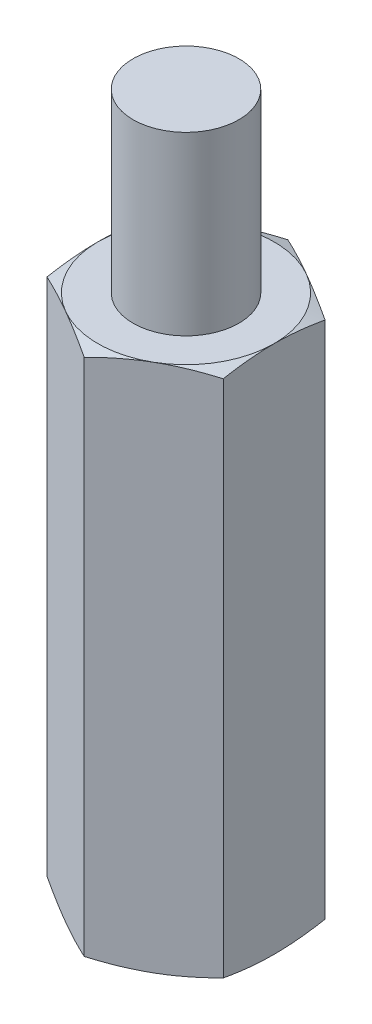
SolidWorks part; units mm, degrees
ref_plane "Front Plane" through (0, 0, 0) normal (0, 0, 1) x (1, 0, 0)
ref_plane "Top Plane" through (0, 0, 0) normal (0, 1, 0) x (1, 0, 0)
ref_plane "Right Plane" through (0, 0, 0) normal (1, 0, 0) x (0, 0, -1)
sketch "Sketch1" plane through (0, 0, 0) normal (0, 1, 0) x (1, 0, 0)
  line L1 (0, 2.8868) -> (-2.5, 1.4434)
  line L2 (-2.5, 1.4434) -> (-2.5, -1.4434)
  line L3 (-2.5, -1.4434) -> (0, -2.8868)
  line L4 (0, -2.8868) -> (2.5, -1.4434)
  line L5 (2.5, -1.4434) -> (2.5, 1.4434)
  line L6 (2.5, 1.4434) -> (0, 2.8868)
  circle A0 centre (0, 0) radius 2.5 construction
  circle A1 centre (0, 0) radius 1.5
  point P1 (2.5, 0)
  dimension "D2" = 3
  dimension "D1" = 5
extrude "Boss-Extrude1" add sketch "Sketch1" along normal blind 15
sketch "Sketch3" plane through (0, 15, 0) normal (0, 1, 0) x (1, 0, 0)
  circle A0 centre (0, 0) radius 2.5
ref_plane "Plane1" through (0, 0, 0) normal (-1, 0, 0) x (0, 0, 1)
sketch "Sketch6" plane through (0, 0, 0) normal (-1, 0, 0) x (0, 0, 1)
  line L0 (2.5, 15) -> (2.8868, 15)
  line L1 (1.4434, 15) -> (2.8868, 15) construction
  line L2 (2.5, 15) -> (-2.5, 15) construction
  line L3 (2.8868, 15) -> (2.8868, 14.8592)
  line L4 (2.8868, 15) -> (2.8868, 0) construction
  line L5 (2.8868, 14.8592) -> (2.5, 15)
  line L6 (0, 15) -> (0, 43.573) construction
  dimension "D1" = 20
  dimension "D2" = 0.3868
revolve "Cut-Revolve1" cut sketch "Sketch6" angle 360 about L6
ref_plane "Plane2" through (0, 7.5, 0) normal (0, 1, 0) x (1, 0, 0)
mirror "Mirror1" about plane through (0, 7.5, 0) normal (0, 1, 0) of "Cut-Revolve1"
sketch "Sketch7" plane through (0, 15, 0) normal (0, 1, 0) x (1, 0, 0)
  circle A0 centre (0, 0) radius 1.5
extrude "Boss-Extrude2" add sketch "Sketch7" along normal blind 5 separate body
